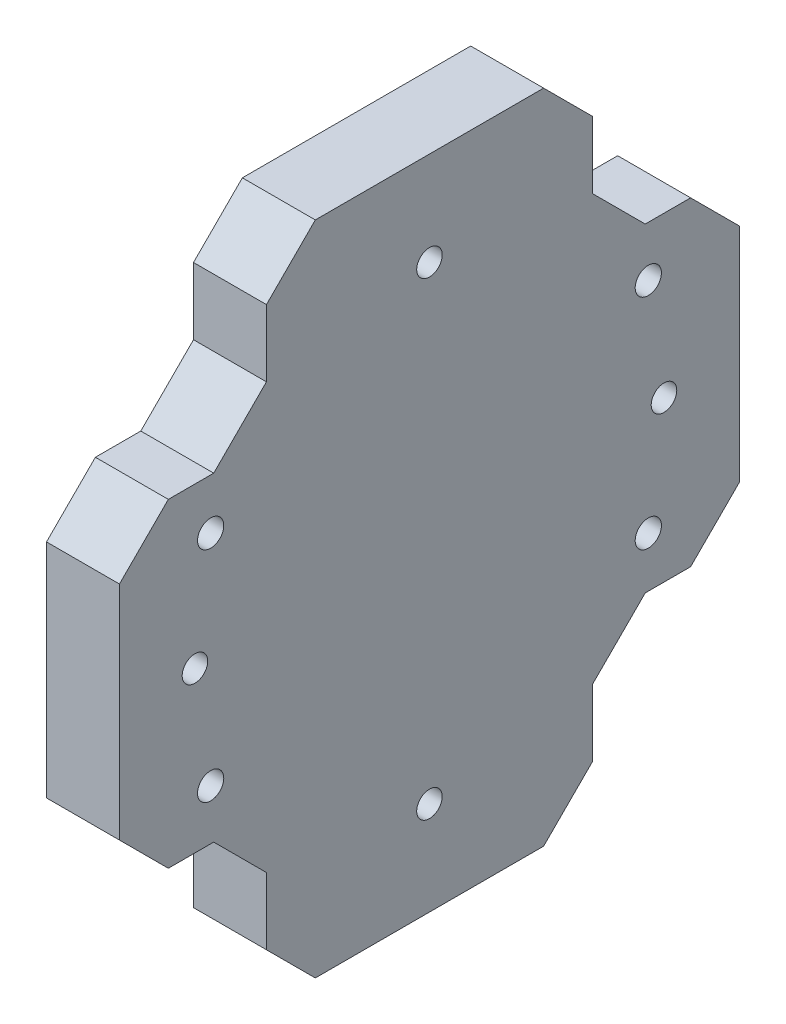
SolidWorks part; units mm, degrees
ref_plane "Front Plane" through (0, 0, 0) normal (1, 0, 0) x (0, 1, 0)
ref_plane "Top Plane" through (0, 0, 0) normal (0, 0, 1) x (0, 1, 0)
ref_plane "Right Plane" through (0, 0, 0) normal (0, 1, 0) x (-1, 0, 0)
sketch "Sketch1" plane through (0, 0, 0) normal (1, 0, 0) x (0, 1, 0)
  line L0 (0, 0) -> (0, 90) construction
  line L5 (0, 0) -> (-90, 0) construction
  line L6 (-45, -15.65) -> (-45, 15.65)
  line L7 (-38.3, 22.35) -> (-29.1274, 22.35)
  line L8 (-29.1274, 22.35) -> (-21.9, 29.5774)
  line L10 (29.1274, 22.35) -> (21.9, 29.5774)
  line L11 (38.3, 22.35) -> (29.1274, 22.35)
  line L12 (45, -15.65) -> (45, 15.65)
  line L14 (29.1274, -22.35) -> (21.9, -29.5774)
  line L15 (38.3, -22.35) -> (29.1274, -22.35)
  line L16 (-29.1274, -22.35) -> (-21.9, -29.5774)
  line L17 (-38.3, -22.35) -> (-29.1274, -22.35)
  line L26 (-45, -15.65) -> (-38.3, -22.35)
  line L27 (-45, 15.65) -> (-38.3, 22.35)
  line L28 (45, 15.65) -> (38.3, 22.35)
  line L29 (45, -15.65) -> (38.3, -22.35)
  line L30 (-21.9, 29.5774) -> (-21.9, 35.8)
  line L31 (-15.2, 42.5) -> (15.2, 42.5)
  line L32 (21.9, 29.5774) -> (21.9, 35.8)
  line L33 (-21.9, -29.5774) -> (-21.9, -35.8)
  line L34 (-15.2, -42.5) -> (15.2, -42.5)
  line L35 (21.9, -29.5774) -> (21.9, -35.8)
  line L36 (-21.9, 35.8) -> (-15.2, 42.5)
  line L37 (21.9, 35.8) -> (15.2, 42.5)
  line L38 (15.2, -42.5) -> (21.9, -35.8)
  line L39 (-21.9, -35.8) -> (-15.2, -42.5)
  line L40 (-40, 15) -> (-40, -15) construction
  line L41 (-32.15, 0) -> (0, 32.15) construction
  line L42 (0, 32.15) -> (32.15, 0) construction
  line L43 (32.15, 0) -> (0, -32.15) construction
  line L44 (0, -32.15) -> (-32.15, 0) construction
  line L45 (-15, 30) -> (15, 30) construction
  line L46 (15, 30) -> (15, -30) construction
  line L47 (15, -30) -> (-15, -30) construction
  line L48 (-15, -30) -> (-15, 30) construction
  circle A8 centre (0, 32.15) radius 1.75
  circle A9 centre (-32.15, 0) radius 1.75
  circle A10 centre (0, -32.15) radius 1.75
  circle A11 centre (32.15, 0) radius 1.75
  circle A16 centre (-15, 30) radius 1.7985
  circle A17 centre (15, 30) radius 1.7985
  circle A18 centre (15, -30) radius 1.7985
  circle A19 centre (-15, -30) radius 1.7985
  point P2 (0, 0)
  point P4 (-45, 22.35)
  point P10 (45, 22.35)
  point P12 (0, 0)
  point P13 (0, 0)
  point P14 (0, 0)
  point P18 (45, -22.35)
  point P19 (0, 0)
  point P20 (-45, -22.35)
  point P23 (0, 0)
  point P24 (0, 0)
  point P25 (0, 0)
  point P72 (21.9, 42.5)
  point P73 (-21.9, -42.5)
  point P74 (-21.9, 42.5)
  point P76 (21.9, -42.5)
  point P77 (-40, 0)
  point P95 (-15, 0)
  point P97 (0, 30)
  dimension "D11" = 3.5
  dimension "D12" = 30
  dimension "D13" = 64.3
  dimension "D16" = 60
  dimension "D17" = 5
  dimension "D1" = 90
  dimension "D2" = 72.8
  dimension "D3" = 43.8
  dimension "D4" = 44.7
  dimension "D5" = 135
  dimension "D6" = 90
  dimension "D14" = 32.15
  dimension "D15" = 85
  dimension "D18" = 30
extrude "Boss-Extrude1" add sketch "Sketch1" along normal blind 10
sketch "Sketch2" plane through (0, 0, 0) normal (-1, 0, 0) x (0, -1, 0)
  circle A0 centre (-15, -30) radius 1.7985 construction
  circle A1 centre (15, -30) radius 1.7985 construction
  circle A2 centre (15, 30) radius 1.7985 construction
  circle A3 centre (-15, 30) radius 1.7985 construction
  circle A4 centre (-15, -30) radius 1.7985 construction
  circle A5 centre (15, -30) radius 1.7985 construction
  circle A6 centre (15, 30) radius 1.7985 construction
  circle A7 centre (-15, 30) radius 1.7985 construction
  circle A8 centre (-15, 30) radius 2.65
  circle A9 centre (15, 30) radius 2.65
  circle A10 centre (15, -30) radius 2.65
  circle A11 centre (-15, -30) radius 2.65
  dimension "D1" = 5.3
extrude "Cut-Extrude1" cut sketch "Sketch2" against normal blind 3.5
